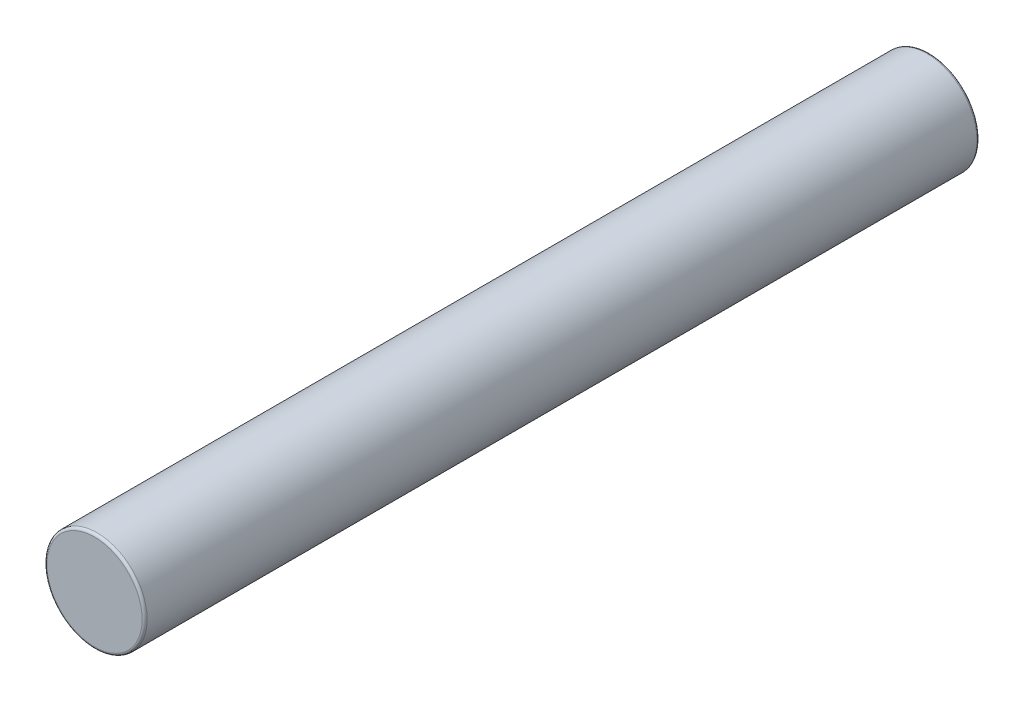
SolidWorks part; units mm, degrees
ref_plane "Front Plane" through (0, 0, 0) normal (0, 0, 1) x (1, 0, 0)
ref_plane "Top Plane" through (0, 0, 0) normal (0, 1, 0) x (1, 0, 0)
ref_plane "Right Plane" through (0, 0, 0) normal (1, 0, 0) x (0, 0, -1)
sketch "Sketch1" plane through (0, 0, 0) normal (0, 0, 1) x (1, 0, 0)
  circle A0 centre (0, 0) radius 1.5
  dimension "D1" = 3
extrude "Boss-Extrude1" add sketch "Sketch1" against normal blind 25
fillet "Fillet1" radius 0.075 2 edges at (1.5, 0, -25) (1.5, 0, 0)
